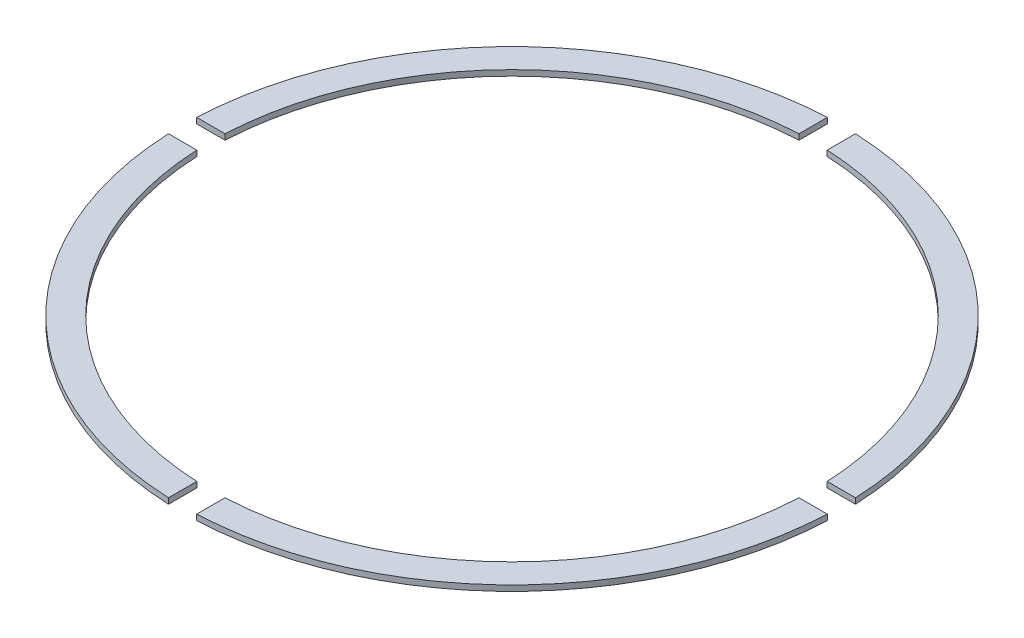
SolidWorks part; units mm, degrees
ref_plane "Front Plane" through (0, 0, 0) normal (0, 0, 1) x (1, 0, 0)
ref_plane "Top Plane" through (0, 0, 0) normal (0, 1, 0) x (1, 0, 0)
ref_plane "Right Plane" through (0, 0, 0) normal (1, 0, 0) x (0, 0, -1)
sketch "Sketch1" plane through (0, 0, 0) normal (0, 1, 0) x (1, 0, 0)
  line L0 (-160, 0) -> (160, 0) construction
  circle A0 centre (0, 0) radius 160
  circle A1 centre (0, 0) radius 175
  dimension "D1" = 320
  dimension "D2" = 350
extrude "Boss-Extrude1" add sketch "Sketch1" along normal mid plane 3
sketch "Sketch2" plane through (0, 0, 0) normal (0, 1, 0) x (1, 0, 0)
  line L0 (-175, 0) -> (175, 0) construction
  line L1 (0, 175) -> (0, -175) construction
  line L3 (183.8046, 7.5) -> (151.1954, 7.5)
  line L4 (183.8046, 7.5) -> (183.8046, -7.5)
  line L5 (183.8046, -7.5) -> (151.1954, -7.5)
  line L6 (151.1954, 7.5) -> (151.1954, -7.5)
  line L7 (183.8046, 7.5) -> (151.1954, -7.5) construction
  line L8 (183.8046, -7.5) -> (151.1954, 7.5) construction
  circle A0 centre (0, 0) radius 175 construction
  circle A1 centre (0, 0) radius 167.5 construction
  circle A2 centre (0, 0) radius 160 construction
  point P7 (167.5, 0)
  dimension "D2" = 7.5
  dimension "D1" = 15
extrude "axis gap" cut sketch "Sketch2" against normal through all both and the other way through all
pattern_circular "CirPattern1" count 4 every 90 about axis through (0, 0, 0) along (0, 1, 0) of "axis gap"
